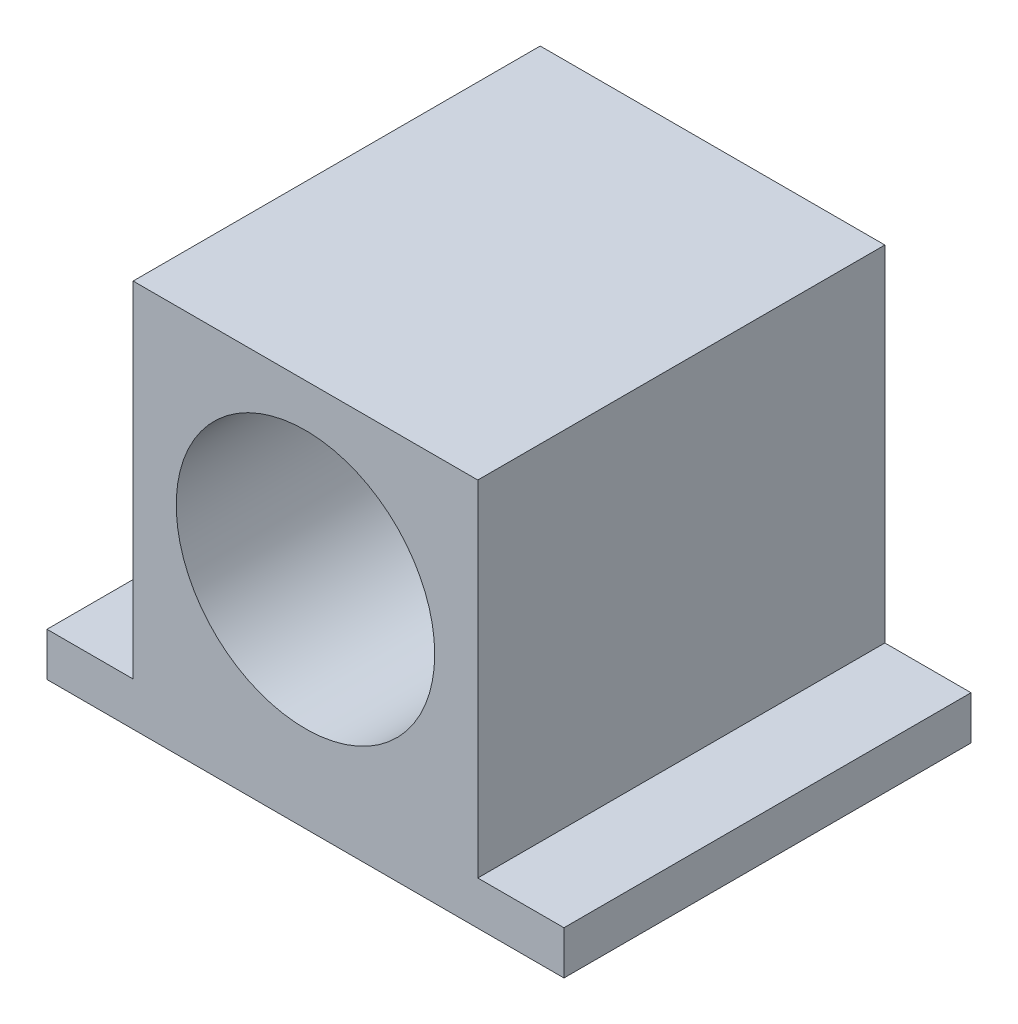
SolidWorks part; units mm, degrees
ref_plane "Front Plane" through (0, 0, 0) normal (0, 0, 1) x (1, 0, 0)
ref_plane "Top Plane" through (0, 0, 0) normal (0, 1, 0) x (1, 0, 0)
ref_plane "Right Plane" through (0, 0, 0) normal (1, 0, 0) x (0, 0, -1)
sketch "Sketch1" plane through (0, 0, 0) normal (0, 0, 1) x (1, 0, 0)
  line L2 (12.7, -12.7) -> (12.7, 12.7)
  line L3 (12.7, 12.7) -> (-12.7, 12.7)
  line L4 (-12.7, -12.7) -> (-12.7, 12.7)
  line L5 (12.7, -12.7) -> (0, 0) construction
  line L6 (12.7, 12.7) -> (-12.7, -12.7) construction
  line L11 (0, 0) -> (-12.7, 12.7) construction
  line L12 (-19.05, -15.908) -> (19.05, -15.908)
  line L13 (-19.05, -15.908) -> (-19.05, -12.7)
  line L14 (-19.05, -12.7) -> (-12.7, -12.7)
  line L15 (12.7, -12.7) -> (19.05, -12.7)
  line L16 (19.05, -12.7) -> (19.05, -15.908)
  circle A0 centre (0, 0) radius 9.525
  dimension "D1" = 19.05
  dimension "D2" = 25.4
  dimension "D3" = 12.7
  dimension "D4" = 28.608
  dimension "D5" = 38.1
  dimension "D6" = 12.7
extrude "Boss-Extrude1" add sketch "Sketch1" along normal blind 30
